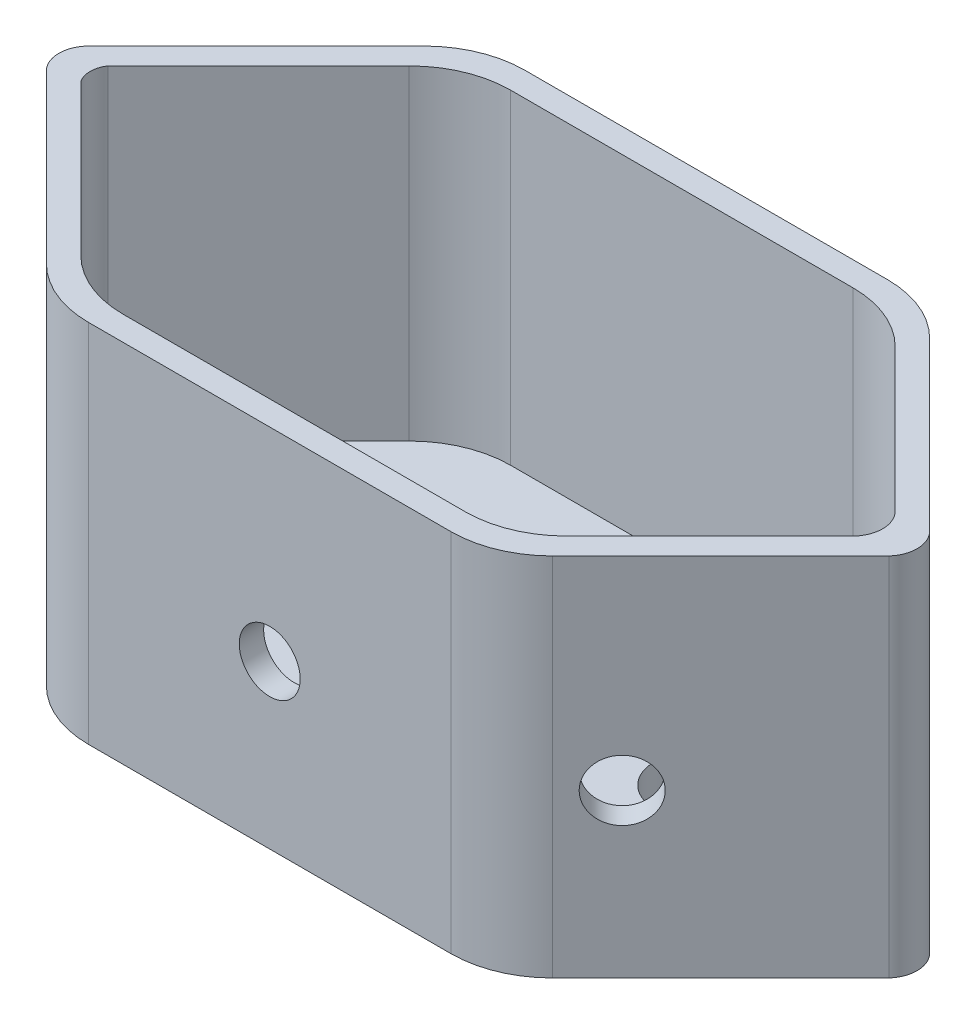
SolidWorks part; units mm, degrees
ref_plane "Plano frontal" through (0, 0, 0) normal (0, 0, 1) x (1, 0, 0)
ref_plane "Plano superior" through (0, 0, 0) normal (0, 1, 0) x (1, 0, 0)
ref_plane "Plano direito" through (0, 0, 0) normal (1, 0, 0) x (0, 0, -1)
sketch "Esboço1" plane through (0, 0, 0) normal (0, 1, 0) x (1, 0, 0)
  line L0 (-11, -10.75) -> (11, -10.75)
  line L1 (-11, 10.75) -> (11, 10.75)
  line L2 (-20.7491, -1.0009) -> (-11, -10.75)
  line L3 (-11, -10.75) -> (11, -10.75)
  line L4 (-11, -10.75) -> (-10.8738, -10.8871)
  line L5 (-20.75, 1) -> (-11, 10.75)
  line L6 (-20.7017, 1.0483) -> (-11, 10.75)
  line L7 (-11, -10.75) -> (-20.7491, -1.0009)
  line L8 (-20.7017, 1.0483) -> (-11, 10.75)
  line L9 (11, -10.75) -> (20.7501, -0.9999)
  line L10 (20.75, 1) -> (11, 10.75)
  line L11 (-11, 10.75) -> (11, 10.75)
  line L12 (20.75, 1) -> (11, 10.75)
  line L13 (20.75, -1) -> (11, -10.75)
  arc A0 (-20.75, -1) -> (-20.75, 1) centre (-19.632, 0) cw
  arc A1 (20.75, 1) -> (20.75, -1) centre (19.632, 0) cw
  arc A2 (20.75, 1) -> (20.7501, -0.9999) centre (19.6319, 0) cw
  arc A3 (-20.7491, -1.0009) -> (-20.75, 1) centre (-19.632, 0.0001) cw
  point P0 (0, 0)
  dimension "D6" = 1.5
  dimension "D9" = 1.5
  dimension "D1" = 21.5
  dimension "D2" = 22
  dimension "D3" = 45
extrude "Ressalto-extrusão1" add sketch "Esboço1" along normal blind 18 contours A3 L2 L0 L9 A1 L10 L1 L5
sketch "Esboço2" plane through (0, 18, 0) normal (0, 1, 0) x (1, 0, 0)
  line L0 (-10.5029, 9.55) -> (9.9721, 9.55)
  line L1 (-11, 10.75) -> (11, 10.75) construction
  line L2 (20.0529, 0) -> (11.5383, 8.5146)
  line L3 (20.75, 1) -> (11, 10.75) construction
  line L4 (11.5383, 8.5146) -> (10.5029, 9.55)
  line L5 (10.5029, 9.55) -> (9.9721, 9.55)
  line L6 (20.0529, 0) -> (10.5029, -9.55)
  line L7 (11, -10.75) -> (20.7501, -0.9999) construction
  line L8 (-10.5029, -9.55) -> (10.5029, -9.55)
  line L9 (-11, -10.75) -> (11, -10.75) construction
  line L10 (-10.5029, -9.55) -> (-20.0529, 0)
  line L11 (-20.0529, 0) -> (-10.5029, 9.55)
  line L12 (-20.7491, -1.0009) -> (-11, -10.75) construction
  line L13 (-20.75, 1) -> (-11, 10.75) construction
  line L14 (-19.0529, 1) -> (-10.5029, 9.55)
  line L15 (10.5029, 9.55) -> (-10.5029, 9.55)
  line L16 (10.5029, 9.55) -> (19.0529, 1)
  line L17 (19.0529, -1) -> (10.5029, -9.55)
  line L18 (10.5029, -9.55) -> (-10.5029, -9.55)
  arc A0 (-19.0529, 1) -> (-19.0529, -1) centre (-18.3896, 0) ccw
  arc A1 (19.0529, 1) -> (19.0529, -1) centre (17.9349, 0) cw
  point P10 (15.2779, -4.775)
  dimension "D9" = 1.2
  dimension "D12" = 1.5
  dimension "D1" = 1.2
  dimension "D2" = 1.2
  dimension "D3" = 1.2
  dimension "D4" = 1.2
  dimension "D5" = 1.2
  dimension "D6" = 1.2
  dimension "D7" = 1
  dimension "D8" = 1
  dimension "D10" = 1
  dimension "D11" = 1
extrude "Corte-extrusão1" cut sketch "Esboço2" against normal blind 16 contours A1 L2 L4 L5 L0 L11 A0 L10 L8 L6
sketch "Esboço3" plane through (0, 0, 9.55) normal (0, 0, -1) x (-1, 0, 0)
  line L0 (10.5029, 18) -> (-10.5029, 18) construction
  circle A0 centre (0, 8) radius 1.5
  point P4 (0, 18)
  dimension "D2" = 3
  dimension "D1" = 10
extrude "Corte-extrusão2" cut sketch "Esboço3" against normal blind 16
sketch "Esboço4" plane through (10.0265, 0, 10.0265) normal (-0.7071, 0, -0.7071) x (-0.7071, 0, 0.7071)
  line L1 (-0.6738, 2) -> (-0.6738, 18) construction
  line L2 (-12.7654, 18) -> (-0.6738, 18) construction
  circle A0 centre (-4.6738, 8) radius 1.5
  dimension "D3" = 3
  dimension "D1" = 10
  dimension "D2" = 4
extrude "Corte-extrusão5" cut sketch "Esboço4" against normal blind 5
sketch "Esboço11" plane through (-10.0265, 0, 10.0265) normal (0.7071, 0, -0.7071) x (-0.7071, 0, -0.7071)
  line L0 (0.6738, 18) -> (13.2415, 18) construction
  line L1 (0.6738, 2) -> (0.6738, 18) construction
  circle A0 centre (4.6738, 8) radius 1.5
  dimension "D1" = 3
  dimension "D2" = 10
  dimension "D3" = 4
extrude "Corte-extrusão6" cut sketch "Esboço11" against normal blind 5
sketch "Esboço16" plane through (0, 2, 0) normal (0, 1, 0) x (1, 0, 0)
  line L0 (-10.5029, -9.55) -> (10.5029, -9.55) construction
  circle A0 centre (-9.75, 0.45) radius 2
  circle A1 centre (9.75, 0.45) radius 2
  circle A2 centre (0, 3.45) radius 2
  dimension "D1" = 4
  dimension "D3" = 4
  dimension "D4" = 4
  dimension "D2" = 13
  dimension "D5" = 19.5
  dimension "D6" = 9.75
  dimension "D7" = 10
  dimension "D8" = 10
extrude "Corte-extrusão7" cut sketch "Esboço16" against normal blind 5
sketch "Esboço17" plane through (0, 2, 0) normal (0, 1, 0) x (1, 0, 0)
  line L0 (-10.5029, -9.55) -> (10.5029, -9.55) construction
  circle A0 centre (-6, -6.55) radius 1.25
  circle A1 centre (6, -6.55) radius 1.25
  dimension "D3" = 2.5
  dimension "D4" = 2.5
  dimension "D1" = 6
  dimension "D2" = 6
  dimension "D5" = 3
  dimension "D6" = 3
extrude "Corte-extrusão8" cut sketch "Esboço17" against normal blind 10
fillet "Filete1" radius 5 1 edges at (-10.5029, 10, -9.55)
fillet "Filete2" radius 5 1 edges at (10.5029, 10, -9.55)
fillet "Filete3" radius 5 1 edges at (-10.5029, 10, 9.55)
fillet "Filete4" radius 5 1 edges at (10.5029, 10, 9.55)
fillet "Filete5" radius 5 1 edges at (-11, 9, -10.75)
fillet "Filete6" radius 5 1 edges at (11, 9, -10.75)
fillet "Filete7" radius 5 1 edges at (-11, 9, 10.75)
fillet "Filete8" radius 5 1 edges at (11, 9, 10.75)
